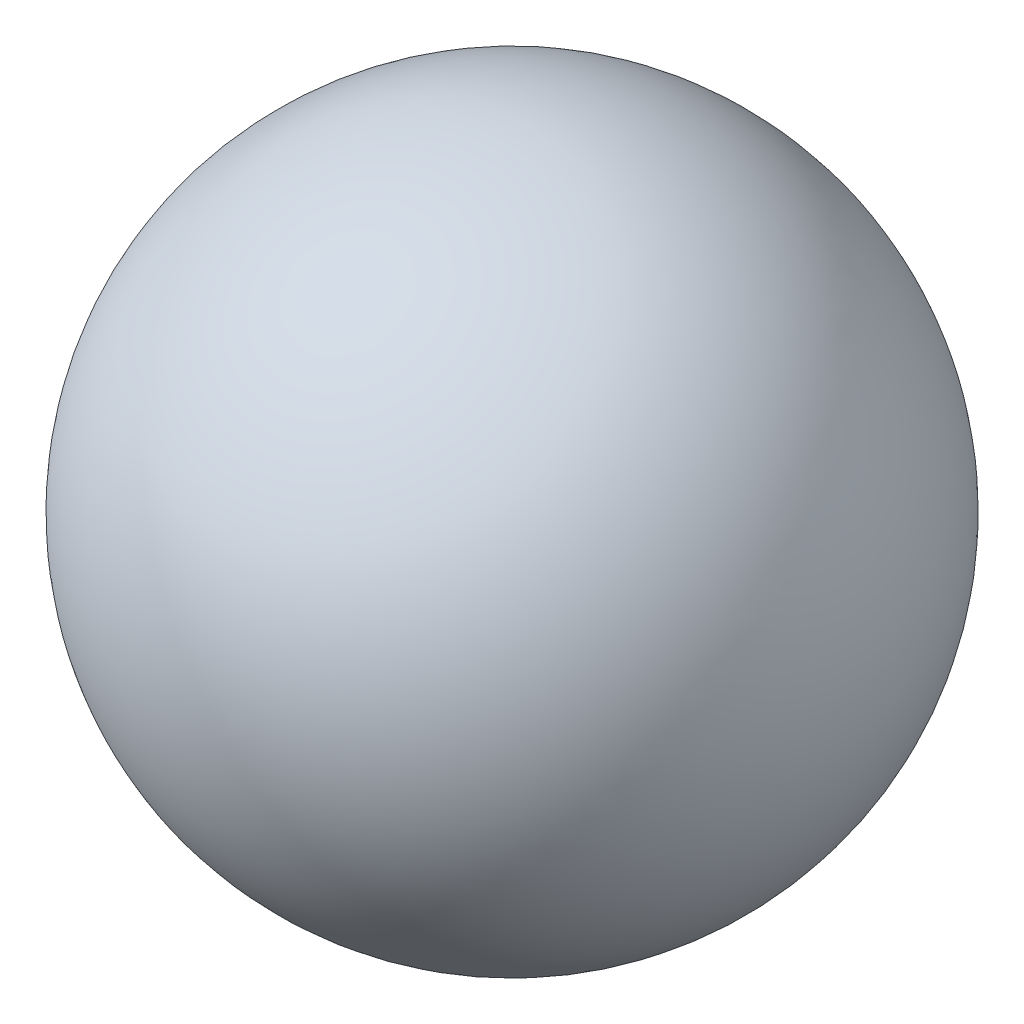
SolidWorks part; units mm, degrees
ref_plane "前视基准面" through (0, 0, 0) normal (0, 0, 1) x (1, 0, 0)
ref_plane "上视基准面" through (0, 0, 0) normal (0, 1, 0) x (1, 0, 0)
ref_plane "右视基准面" through (0, 0, 0) normal (1, 0, 0) x (0, 0, -1)
sketch "草图1" plane through (0, 0, 0) normal (0, 1, 0) x (1, 0, 0)
  line L0 (0, 0) -> (0, 17)
  arc A0 (0, 0) -> (0, 17) centre (0, 8.5) ccw
  dimension "D1" = 17
revolve "旋转1" add sketch "草图1" angle 360 about L0
